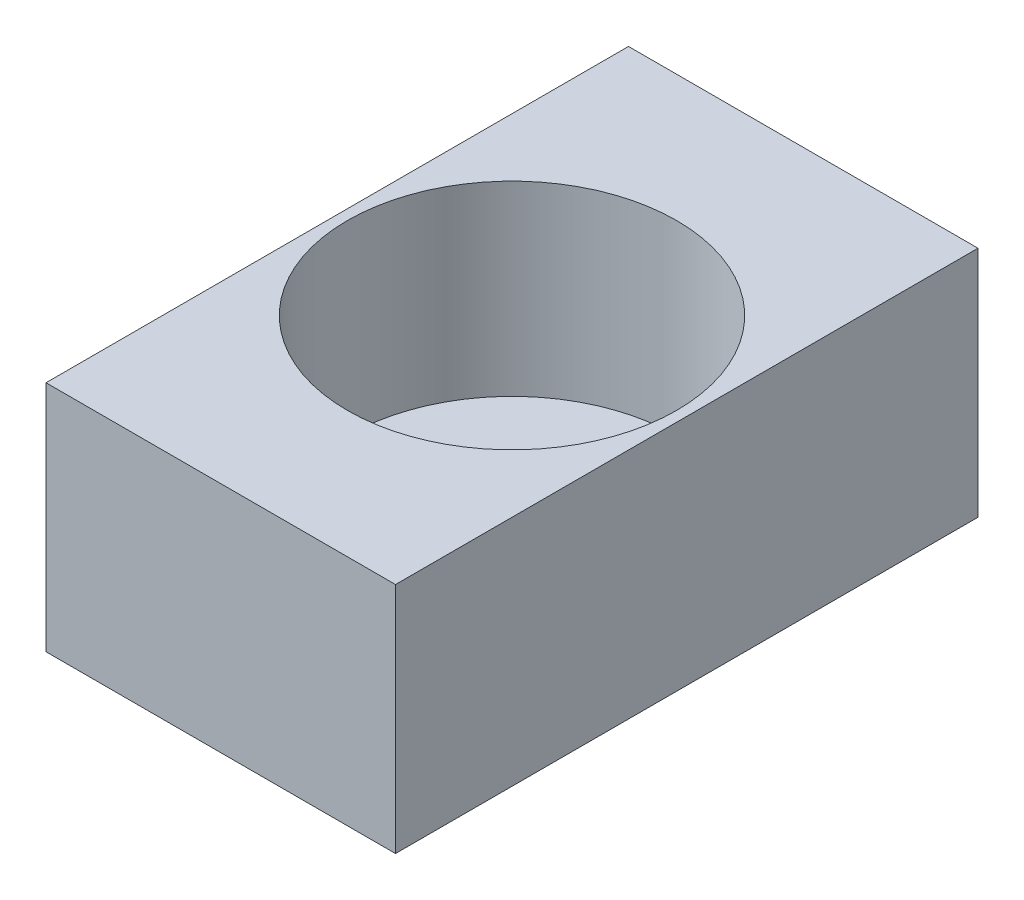
SolidWorks part; units mm, degrees
ref_plane "Front Plane" through (0, 0, 0) normal (0, 0, 1) x (1, 0, 0)
ref_plane "Top Plane" through (0, 0, 0) normal (0, 1, 0) x (1, 0, 0)
ref_plane "Right Plane" through (0, 0, 0) normal (1, 0, 0) x (0, 0, -1)
sketch "Sketch2" plane through (0, 0, 0) normal (0, 0, 1) x (1, 0, 0)
  line L1 (0, 0) -> (30, 0)
  line L2 (0, 0) -> (0, 20)
  line L3 (0, 20) -> (30, 20)
  line L4 (30, 0) -> (30, 20)
  dimension "D1" = 20
  dimension "D2" = 30
extrude "Boss-Extrude1" add sketch "Sketch2" along normal blind 50
sketch "Sketch3" plane through (0, 20, 0) normal (0, 1, 0) x (1, 0, 0)
  line L0 (15, 0) -> (15, -50) construction
  line L1 (30, 0) -> (0, 0) construction
  line L2 (30, -50) -> (0, -50) construction
  line L3 (0, -25) -> (30, -25) construction
  line L4 (0, -50) -> (0, 0) construction
  line L5 (30, -50) -> (30, 0) construction
  circle A0 centre (15, -25) radius 14.125
  dimension "D1" = 28.25
extrude "Cut-Extrude1" cut sketch "Sketch3" against normal blind 16
sketch "Sketch4" plane through (0, 4, 0) normal (0, 1, 0) x (1, 0, 0)
  circle A0 centre (15, -25) radius 3.25
  dimension "D1" = 6.5
extrude "Cut-Extrude2" cut sketch "Sketch4" against normal blind 16
equation "\"L\"= 50mm"
equation "\"b\" = 30mm"
equation "\"h\"= 20mm"
